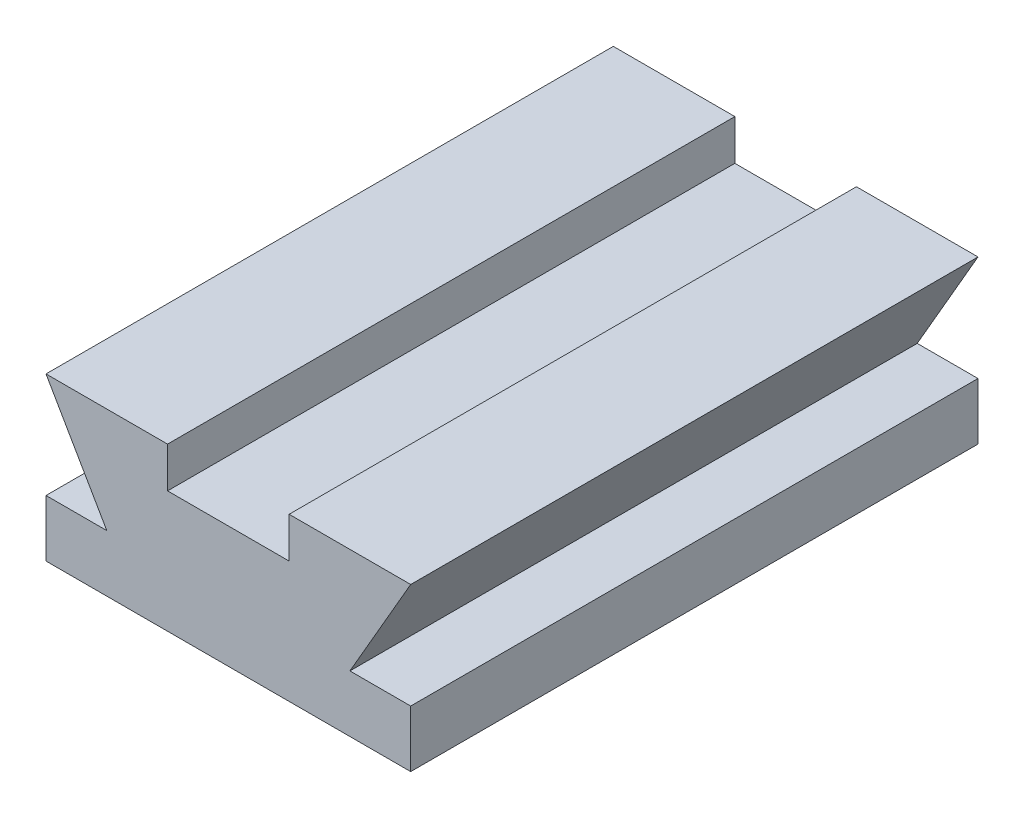
SolidWorks part; units mm, degrees
ref_plane "Front Plane" through (0, 0, 0) normal (0, 0, 1) x (1, 0, 0)
ref_plane "Top Plane" through (0, 0, 0) normal (0, 1, 0) x (1, 0, 0)
ref_plane "Right Plane" through (0, 0, 0) normal (1, 0, 0) x (0, 0, -1)
sketch "Sketch1" plane through (0, 0, 0) normal (0, 1, 0) x (1, 0, 0)
  line L1 (-0.6173, 1.8518) -> (3.8827, 1.8518)
  line L2 (-0.6173, 1.8518) -> (-0.6173, 8.8518)
  line L3 (-0.6173, 8.8518) -> (3.8827, 8.8518)
  line L4 (3.8827, 1.8518) -> (3.8827, 8.8518)
extrude "Boss-Extrude1" add sketch "Sketch1" along normal blind 2 contours L3 L4 L1 L2
sketch "Sketch2" plane through (0, 2, 0) normal (0, 1, 0) x (1, 0, 0)
  line L0 (-0.6173, 8.8518) -> (3.8827, 8.8518) construction
  line L1 (2.3827, 1.8518) -> (0.8827, 1.8518)
  line L2 (2.3827, 1.8518) -> (2.3827, 8.8518)
  line L3 (2.3827, 8.8518) -> (0.8827, 8.8518)
  line L4 (0.8827, 1.8518) -> (0.8827, 8.8518)
  line L5 (-0.6173, 1.8518) -> (3.8827, 1.8518) construction
  line L6 (-0.6173, 1.8518) -> (-0.6173, 8.8518) construction
  line L7 (3.8827, 1.8518) -> (3.8827, 8.8518) construction
  dimension "D1" = 1.5
  dimension "D2" = 1.5
extrude "Cut-Extrude3" cut sketch "Sketch2" against normal blind 0.5
sketch "Sketch3" plane through (0, 0, -8.8518) normal (0, 0, -1) x (-1, 0, 0)
  line L0 (0.6173, 2) -> (-0.1327, 0.701)
  line L1 (-0.1327, 0.701) -> (0.6173, 0.701)
  line L3 (0.6173, 0) -> (-3.8827, 0) construction
  line L4 (0.6173, 2) -> (-0.8827, 2) construction
  line L5 (-3.8827, 2) -> (-3.1327, 0.701)
  line L6 (-3.1327, 0.701) -> (-3.8827, 0.701)
  line L9 (-2.3827, 2) -> (-3.8827, 2) construction
  line L12 (-3.8827, 2) -> (-3.8827, 0.701)
  line L13 (-3.8827, 2) -> (-3.8827, 0) construction
  line L15 (0.6173, 2) -> (0.6173, 0.701)
  line L16 (0.6173, 2) -> (0.6173, 0) construction
  point P2 (0, 0)
  point P3 (-0.3517, 1.8419)
  point P5 (0, 0)
  point P6 (0, 0)
  point P13 (0, 0)
  point P21 (0, 0)
  point P22 (0, 0)
  point P23 (-3.2603, 1.4843)
  point P24 (-3.2603, 1.7068)
  point P25 (-3.2524, 1.5796)
  point P26 (-3.308, 1.8101)
  point P27 (0, 0)
  point P28 (0, 0)
  point P29 (0, 0)
  point P30 (0, 0)
  point P31 (0, 0)
  dimension "D1" = 60
  dimension "D2" = 60
  dimension "D3" = 3
extrude "Cut-Extrude4" cut sketch "Sketch3" against normal through all
